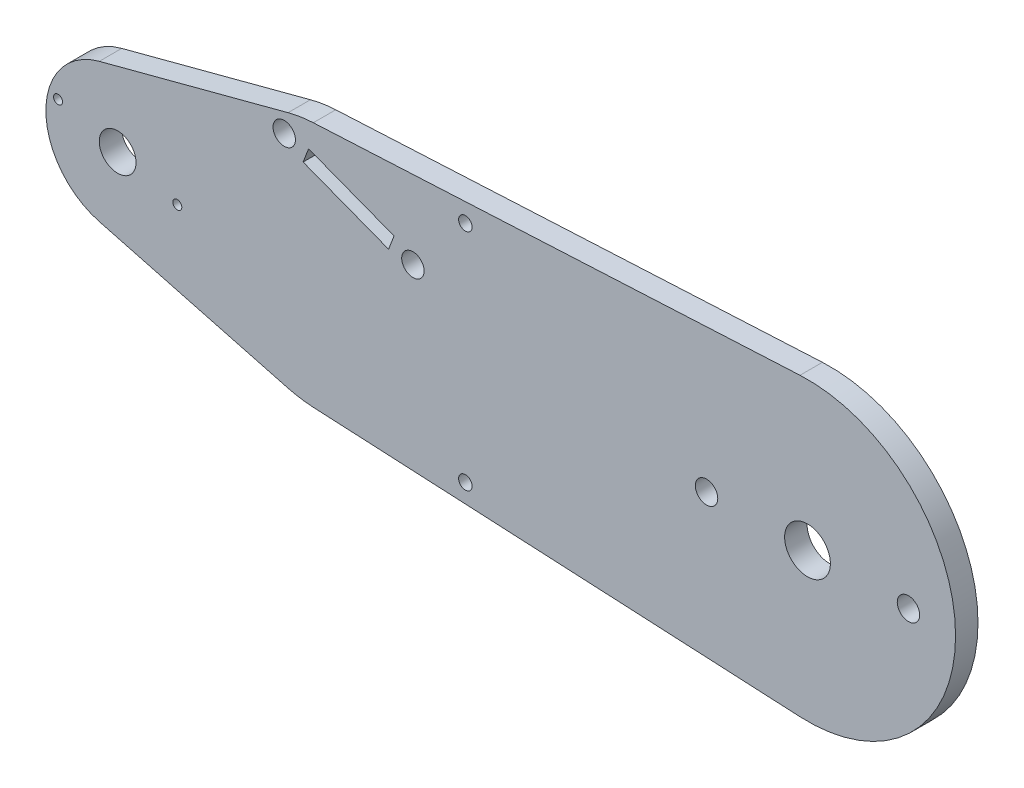
SolidWorks part; units mm, degrees
ref_plane "Front Plane" through (0, 0, 0) normal (0, 0, 1) x (1, 0, 0)
ref_plane "Top Plane" through (0, 0, 0) normal (0, 1, 0) x (1, 0, 0)
ref_plane "Right Plane" through (0, 0, 0) normal (1, 0, 0) x (0, 0, -1)
sketch "Sketch1" plane through (0, 0, 0) normal (0, 0, 1) x (1, 0, 0)
  line L0 (-51.875, 0) -> (51.875, 0) construction
  line L3 (-58.2658, 27.4648) -> (50.206, 32.9578)
  line L4 (-58.2658, -27.4648) -> (50.206, -32.9578)
  line L5 (-46.875, 0) -> (-56.875, 0) construction
  line L6 (-46.875, -18) -> (-56.875, -18) construction
  line L7 (-46.875, 18) -> (-56.875, 18) construction
  line L8 (-51.875, 0) -> (-101.875, 0) construction
  line L9 (-105.9639, 15.4687) -> (-63.9028, 26.5868)
  line L10 (-105.9639, -15.4687) -> (-63.9028, -26.5868)
  arc A3 (50.206, -32.9578) -> (50.206, 32.9578) centre (51.875, 0) ccw
  circle A5 centre (51.875, 0) radius 5.1
  arc A6 (-46.875, -18) -> (-46.875, 18) centre (-46.875, 0) ccw construction
  arc A7 (-56.875, 18) -> (-56.875, -18) centre (-56.875, 0) ccw construction
  arc A8 (-58.2658, 27.4648) -> (-58.2658, -27.4648) centre (-56.875, 0) ccw
  circle A9 centre (-101.875, 0) radius 4.1
  circle A10 centre (-101.875, 0) radius 16
  point P9 (-51.875, 0)
  dimension "D1" = 103.75
  dimension "D2" = 66
  dimension "D3" = 8.2
  dimension "D5" = 10.2
  dimension "D7" = 18
  dimension "D8" = 55
  dimension "D9" = 32
  dimension "D4" = 51.875
  dimension "D6" = 10
  dimension "D10" = 50
extrude "Boss-Extrude1" add sketch "Sketch1" along normal blind 5 contours A10 L10 A8 L9 | A10 A9 | L3 A8 L4 A3 A5
sketch "Sketch7" plane through (0, 0, 5) normal (0, 0, 1) x (1, 0, 0)
  line L0 (51.875, 5) -> (51.875, -5) construction
  line L1 (51.875, 0) -> (29.375, 0) construction
  circle A0 centre (51.875, 0) radius 5 construction
  circle A1 centre (29.375, 0) radius 2.5
  circle A2 centre (74.375, 0) radius 2.5
  dimension "D1" = 5
  dimension "D2" = 22.5
extrude "Cut-Extrude1" cut sketch "Sketch7" against normal blind 7
sketch "Sketch8" plane through (0, 0, 5) normal (0, 0, 1) x (1, 0, 0)
  line L0 (-84.375, 0) -> (-24.375, 0) construction
  line L1 (-24.375, 0) -> (-24.375, 25) construction
  line L3 (-26.375, 28.4641) -> (-28.375, 25)
  line L4 (-28.375, 25) -> (-26.375, 21.5359)
  line L5 (-26.375, 21.5359) -> (-22.375, 21.5359)
  line L6 (-22.375, 21.5359) -> (-20.375, 25)
  line L7 (-20.375, 25) -> (-22.375, 28.4641)
  line L8 (-22.375, 28.4641) -> (-26.375, 28.4641)
  line L9 (-25.9916, 27.8) -> (-27.6082, 25)
  line L10 (-27.6082, 25) -> (-25.9916, 22.2)
  line L11 (-25.9916, 22.2) -> (-22.7584, 22.2)
  line L12 (-22.7584, 22.2) -> (-21.1418, 25)
  line L13 (-21.1418, 25) -> (-22.7584, 27.8)
  line L14 (-22.7584, 27.8) -> (-25.9916, 27.8)
  arc A0 (-58.2658, 27.4648) -> (-58.2658, -27.4648) centre (-56.875, 0) ccw construction
  circle A1 centre (-24.375, 25) radius 3.4641 construction
  circle A2 centre (-24.375, 25) radius 2.8 construction
  dimension "D1" = 8
  dimension "D2" = 5.6
  dimension "D3" = 25
  dimension "D4" = 60
extrude "Boss-Extrude6" add sketch "Sketch8" against normal blind 8
sketch "Sketch9" plane through (0, 0, 5) normal (0, 0, 1) x (1, 0, 0)
  line L0 (-24.375, 27.4682) -> (-24.375, 22.5318) construction
  line L1 (-22.95, 27.4682) -> (-25.8, 27.4682) construction
  line L2 (-25.8, 22.5318) -> (-22.95, 22.5318) construction
  circle A0 centre (-24.375, 25) radius 1.5
  dimension "D1" = 3
extrude "Cut-Extrude2" cut sketch "Sketch9" against normal blind 6
mirror "Mirror1" about plane through (0, 0, 0) normal (0, 1, 0) of "Boss-Extrude6"
mirror "Mirror2" about plane through (0, 0, 0) normal (0, 1, 0) of "Cut-Extrude2"
sketch "Sketch10" plane through (0, 0, 5) normal (0, 0, 1) x (1, 0, 0)
  line L0 (51.875, 0) -> (-101.875, 0) construction
  line L1 (-41.6054, 11.695) -> (-60.2795, 18.8558)
  line L2 (-60.2795, 18.8558) -> (-59.2054, 21.657)
  line L3 (-59.2054, 21.657) -> (-40.5313, 14.4961)
  line L4 (-40.5313, 14.4961) -> (-41.6054, 11.695)
  line L5 (-50.9424, 15.2754) -> (-49.8683, 18.0765) construction
  line L6 (-50.9424, 15.2754) -> (-56.8, 0) construction
  line L7 (-41.6054, 11.695) -> (-46.09, 0) construction
  line L8 (-60.2795, 18.8558) -> (-67.6186, 0) construction
  line L9 (-25, 0) -> (-81.9162, 21.8253) construction
  line L10 (-41.0683, 13.0956) -> (-36.0683, 11.1782) construction
  line L11 (-105.9639, 15.4687) -> (-63.9028, 26.5868) construction
  circle A0 centre (-36.0683, 11.1782) radius 2.5
  circle A1 centre (-64.7424, 22.1737) radius 2.5
  point P10 (-25, 0)
  dimension "D7" = 5
  dimension "D1" = 31.8
  dimension "D2" = 20
  dimension "D3" = 3
  dimension "D4" = 16.36
  dimension "D5" = 34.2564
  dimension "D6" = 20.98
  dimension "D8" = 5
extrude "Boss-Extrude7" add sketch "Sketch10" along normal blind 5
sketch "Sketch12" plane through (0, 0, 10) normal (0, 0, 1) x (1, 0, 0)
  line L0 (-59.2054, 21.657) -> (-41.6054, 11.695) construction
  line L1 (-59.3205, 21.9153) -> (-40.2729, 14.6112)
  line L2 (-40.2729, 14.6112) -> (-41.4902, 11.4367)
  line L3 (-41.4902, 11.4367) -> (-60.5378, 18.7407)
  line L4 (-60.5378, 18.7407) -> (-59.3205, 21.9153)
  line L5 (-40.5313, 14.4961) -> (-59.2054, 21.657) construction
  line L6 (-59.2054, 21.657) -> (-60.2795, 18.8558) construction
  line L7 (-60.2795, 18.8558) -> (-41.6054, 11.695) construction
  line L8 (-41.6054, 11.695) -> (-40.5313, 14.4961) construction
  line L9 (-50.4054, 16.676) -> (-49.7967, 18.2633) construction
  line L10 (-41.6054, 11.695) -> (-40.5313, 14.4961) construction
  circle A0 centre (-36.0683, 11.1782) radius 2.5
  circle A1 centre (-64.7424, 22.1737) radius 2.5
  dimension "D5" = 5
  dimension "D1" = 0.2
  dimension "D2" = 0.2
  dimension "D3" = 0.2
  dimension "D4" = 0.2
extrude "Cut-Extrude4" cut sketch "Sketch12" against normal blind 10
sketch "Sketch11" plane through (0, 0, 5) normal (0, 0, 1) x (1, 0, 0)
  line L0 (-105.9639, -15.4687) -> (-101.875, 0) construction
  line L1 (-88.5816, -3.5139) -> (-101.875, 0) construction
  circle A0 centre (-101.875, 0) radius 13.75 construction
  circle A3 centre (-88.5816, -3.5139) radius 1
  circle A4 centre (-115.1684, 3.5139) radius 1
  dimension "D2" = 2
  dimension "D3" = 27.5
  dimension "D1" = 90
extrude "Cut-Extrude3" cut sketch "Sketch11" against normal blind 6
sketch "Sketch13" plane through (0, 0, 0) normal (0, 0, -1) x (-1, 0, 0)
  line L0 (105.9639, 15.4687) -> (63.9028, 26.5868) construction
  line L1 (105.9639, -15.4687) -> (63.9028, -26.5868) construction
  line L2 (58.2658, -27.4648) -> (-50.206, -32.9578) construction
  line L3 (58.2658, 27.4648) -> (-50.206, 32.9578) construction
  line L4 (105.9639, 15.4687) -> (63.9028, 26.5868)
  line L5 (105.9639, -15.4687) -> (63.9028, -26.5868)
  line L6 (58.2658, -27.4648) -> (-50.206, -32.9578)
  line L7 (58.2658, 27.4648) -> (-50.206, 32.9578)
  arc A0 (63.9028, 26.5868) -> (58.2658, 27.4648) centre (56.875, 0) ccw construction
  arc A1 (105.9639, -15.4687) -> (105.9639, 15.4687) centre (101.875, 0) ccw construction
  arc A2 (58.2658, -27.4648) -> (63.9028, -26.5868) centre (56.875, 0) ccw construction
  arc A3 (-50.206, 32.9578) -> (-50.206, -32.9578) centre (-51.875, 0) ccw construction
  arc A4 (63.9028, 26.5868) -> (58.2658, 27.4648) centre (56.875, 0) ccw
  arc A5 (105.9639, -15.4687) -> (105.9639, 15.4687) centre (101.875, 0) ccw
  arc A6 (58.2658, -27.4648) -> (63.9028, -26.5868) centre (56.875, 0) ccw
  arc A7 (-50.206, 32.9578) -> (-50.206, -32.9578) centre (-51.875, 0) ccw
extrude "Cut-Extrude5" cut sketch "Sketch13" along normal blind 5
